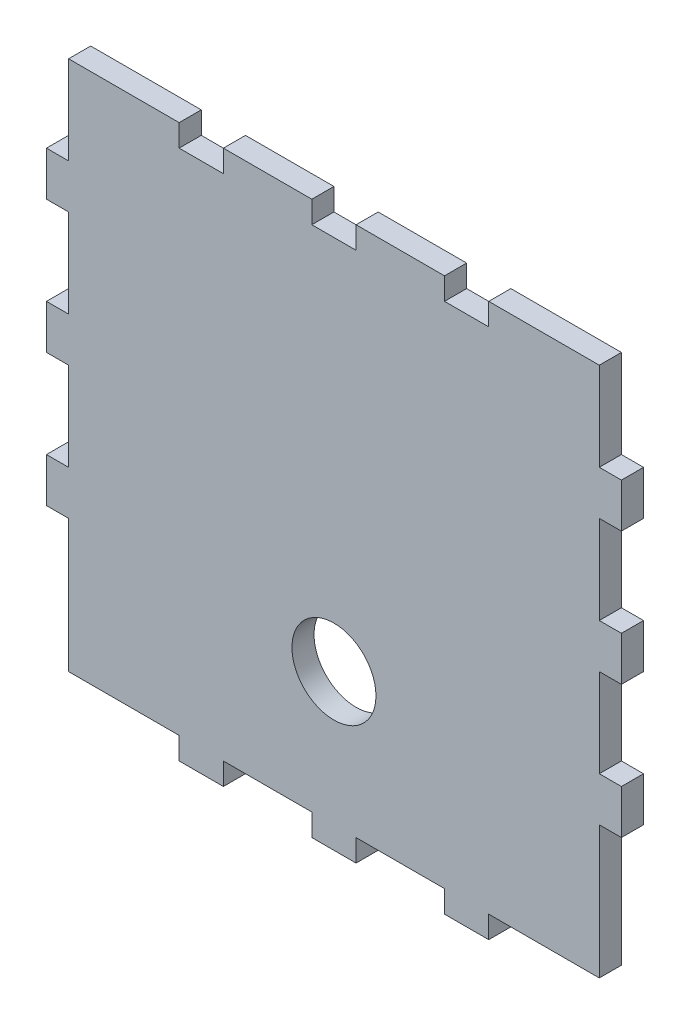
SolidWorks part; units mm, degrees
ref_plane "Ön Düzlem" through (0, 0, 0) normal (0, 0, 1) x (1, 0, 0)
ref_plane "Üst Düzlem" through (0, 0, 0) normal (0, 1, 0) x (1, 0, 0)
ref_plane "Sağ Düzlem" through (0, 0, 0) normal (1, 0, 0) x (0, 0, -1)
sketch "Sketch1" plane through (0, 0, 0) normal (0, 0, 1) x (1, 0, 0)
  line L0 (-35, 60) -> (-35, 55)
  line L1 (-60, -60) -> (-35, -60)
  line L2 (-60, -60) -> (-60, -30)
  line L3 (-60, 60) -> (-35, 60)
  line L4 (60, -60) -> (60, -30)
  line L5 (-60, -60) -> (60, 60) construction
  line L6 (-60, 60) -> (60, -60) construction
  line L7 (-35, 55) -> (-25, 55)
  line L8 (-25, 55) -> (-25, 60)
  line L15 (-5, 55) -> (5, 55)
  line L16 (-5, 60) -> (-5, 55)
  line L17 (5, 55) -> (5, 60)
  line L21 (25, 55) -> (35, 55)
  line L22 (25, 60) -> (25, 55)
  line L23 (35, 55) -> (35, 60)
  line L24 (-60, 40) -> (-65, 40)
  line L25 (-65, 40) -> (-65, 30)
  line L26 (-65, 30) -> (-60, 30)
  line L27 (60, 40) -> (65, 40)
  line L28 (65, 40) -> (65, 30)
  line L29 (65, 30) -> (60, 30)
  line L30 (-65, 10) -> (-65, 0)
  line L31 (-60, 10) -> (-65, 10)
  line L32 (-65, 0) -> (-60, 0)
  line L33 (65, 0) -> (60, 0)
  line L34 (65, 10) -> (65, 0)
  line L35 (60, 10) -> (65, 10)
  line L36 (-65, -20) -> (-65, -30)
  line L37 (-60, -20) -> (-65, -20)
  line L38 (-65, -30) -> (-60, -30)
  line L39 (65, -30) -> (60, -30)
  line L40 (65, -20) -> (65, -30)
  line L41 (60, -20) -> (65, -20)
  line L42 (-25, 60) -> (-5, 60)
  line L43 (5, 60) -> (25, 60)
  line L44 (35, 60) -> (60, 60)
  line L45 (35, -60) -> (60, -60)
  line L46 (5, -60) -> (25, -60)
  line L47 (-25, -60) -> (-5, -60)
  line L48 (-60, -20) -> (-60, 0)
  line L49 (-60, 10) -> (-60, 30)
  line L50 (60, -20) -> (60, 0)
  line L51 (60, 10) -> (60, 30)
  line L52 (60, 40) -> (60, 60)
  line L53 (-60, 40) -> (-60, 60)
  line L54 (-65, -80) -> (-65, -90) [skipped]
  line L55 (-60, -80) -> (-65, -80) [skipped]
  line L56 (-65, -90) -> (-60, -90) [skipped]
  line L57 (65, -90) -> (60, -90) [skipped]
  line L58 (65, -80) -> (65, -90) [skipped]
  line L59 (60, -80) -> (65, -80) [skipped]
  line L60 (65, -60) -> (60, -60) [skipped]
  line L61 (65, -50) -> (65, -60) [skipped]
  line L62 (60, -50) -> (65, -50) [skipped]
  line L63 (-60, -50) -> (-65, -50) [skipped]
  line L64 (-65, -50) -> (-65, -60) [skipped]
  line L65 (-65, -60) -> (-60, -60) [skipped]
  line L66 (-35, -60) -> (-35, -65)
  line L67 (-35, -65) -> (-25, -65)
  line L68 (-25, -65) -> (-25, -60)
  line L69 (5, -65) -> (5, -60)
  line L70 (-5, -65) -> (5, -65)
  line L71 (-5, -60) -> (-5, -65)
  line L72 (35, -65) -> (35, -60)
  line L73 (25, -65) -> (35, -65)
  line L74 (25, -60) -> (25, -65)
  circle A0 centre (0, -30) radius 9.5
  point P0 (0, 0)
  dimension "D18" = 19
  dimension "D1" = 120
  dimension "D2" = 25
  dimension "D3" = 5
  dimension "D4" = 10
  dimension "D6" = 20
  dimension "D7" = 5
  dimension "D8" = 10
  dimension "D9" = 20
  dimension "D11" = 20
  dimension "D12" = 120
  dimension "D13" = 10
  dimension "D14" = 5
  dimension "D15" = 25
  dimension "D17" = 20
  dimension "D19" = 30
  dimension "D5" = 3
  dimension "D10" = 5
  dimension "D16" = 3
extrude "Boss-Extrude1" add sketch "Sketch1" along normal blind 5
